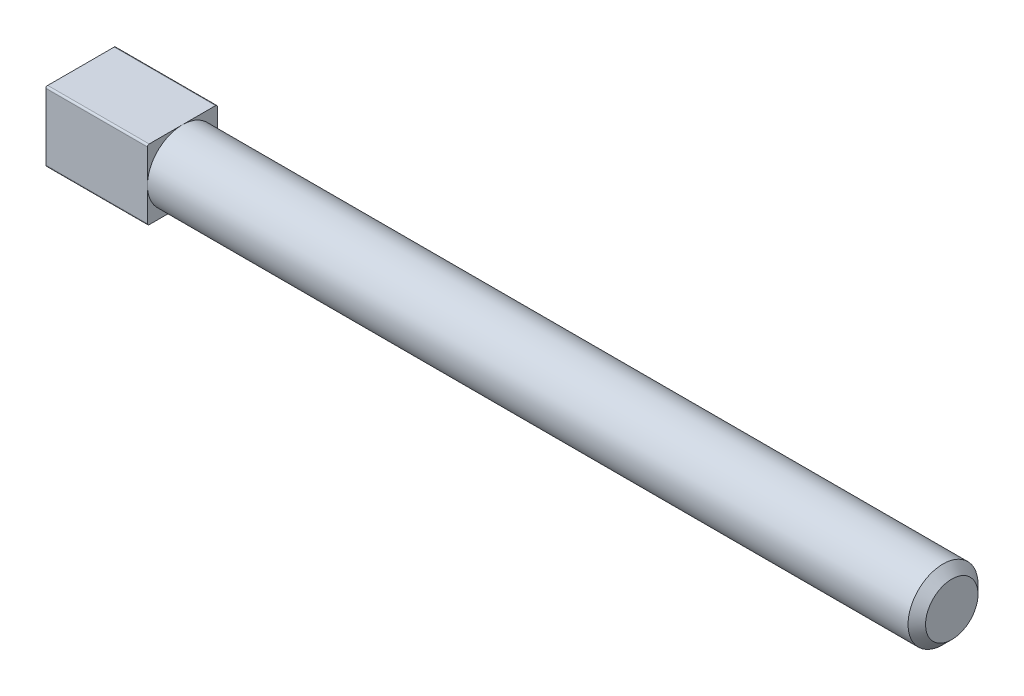
SolidWorks part; units mm, degrees
ref_plane "前视基准面" through (0, 0, 0) normal (0, 0, 1) x (1, 0, 0)
ref_plane "上视基准面" through (0, 0, 0) normal (0, 1, 0) x (1, 0, 0)
ref_plane "右视基准面" through (0, 0, 0) normal (1, 0, 0) x (0, 0, -1)
sketch "草图1" plane through (0, 0, 0) normal (1, 0, 0) x (0, 0, -1)
  line L0 (2, -2) -> (2, 2)
  line L1 (2, -2) -> (-2, -2)
  line L2 (2, 2) -> (-2, 2)
  line L3 (-2, -2) -> (-2, 2)
  line L4 (2, -2) -> (-2, 2) construction
  line L5 (2, 2) -> (-2, -2) construction
  point P1 (0, 0)
  dimension "D1" = 4
  dimension "D2" = 4
extrude "凸台-拉伸1" add sketch "草图1" along normal blind 6
sketch "草图2" plane through (6, 0, 0) normal (1, 0, 0) x (0, 0, -1)
  circle A0 centre (0, 0) radius 2
extrude "凸台-拉伸2" add sketch "草图2" along normal blind 44
chamfer "倒角1" distance 0.5 angle 45 1 edges at (50, 0, -2)
chamfer "倒角2" distance 0.2 angle 45 4 edges at (0, 0, -2) (0, 2, 0) (0, 0, 2) (0, -2, 0)
fillet "圆角1" radius 0.1 4 edges at (3.1, 2, -2) (3.1, -2, -2) (3.1, -2, 2) (3.1, 2, 2)
